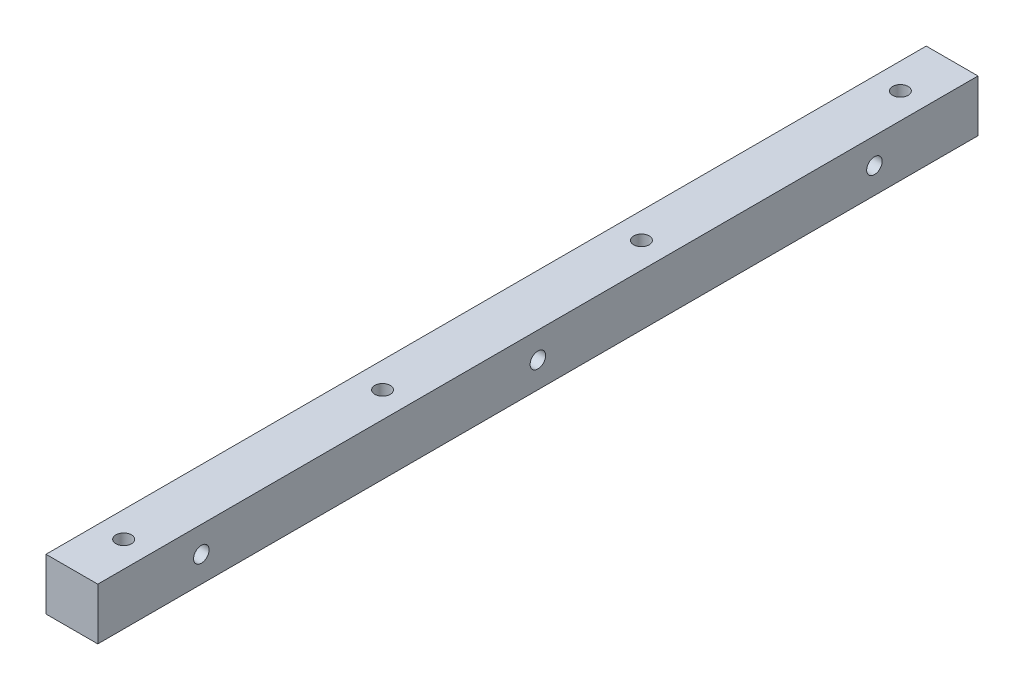
SolidWorks part; units mm, degrees
ref_plane "Front Plane" through (0, 0, 0) normal (0, 0, 1) x (1, 0, 0)
ref_plane "Top Plane" through (0, 0, 0) normal (0, 1, 0) x (1, 0, 0)
ref_plane "Right Plane" through (0, 0, 0) normal (1, 0, 0) x (0, 0, -1)
sketch "Sketch1" plane through (0, 0, 0) normal (0, 0, 1) x (1, 0, 0)
  line L1 (0, 0) -> (10, 0)
  line L2 (0, 0) -> (0, 10)
  line L3 (0, 10) -> (10, 10)
  line L4 (10, 0) -> (10, 10)
  dimension "D1" = 10
  dimension "D2" = 10
extrude "Extrude1" add sketch "Sketch1" along normal blind 170
sketch "Sketch4" plane through (0, 10, 0) normal (0, 1, 0) x (-1, 0, 0)
  line L1 (0, 5.5) -> (0, -5.5) construction
  circle A0 centre (-5, 10) radius 1.5
  dimension "D1" = 3
  dimension "D2" = 5
  dimension "D3" = 10
extrude "Cut-Extrude3" cut sketch "Sketch4" against normal through all
pattern_linear "LPattern1" count 4 spacing 50 along (0, 0, 1) of "Cut-Extrude3"
sketch "Sketch5" plane through (0, 0, 0) normal (-1, 0, 0) x (0, 0, 1)
  line L0 (170, 10) -> (170, 0) construction
  circle A0 centre (20, 5) radius 1.5
  circle A1 centre (85, 5) radius 1.5
  circle A2 centre (150, 5) radius 1.5
  dimension "D6" = 3
  dimension "D1" = 5
  dimension "D2" = 20
  dimension "D3" = 20
  dimension "D4" = 65
  dimension "D5" = 65
extrude "Cut-Extrude4" cut sketch "Sketch5" against normal through all
